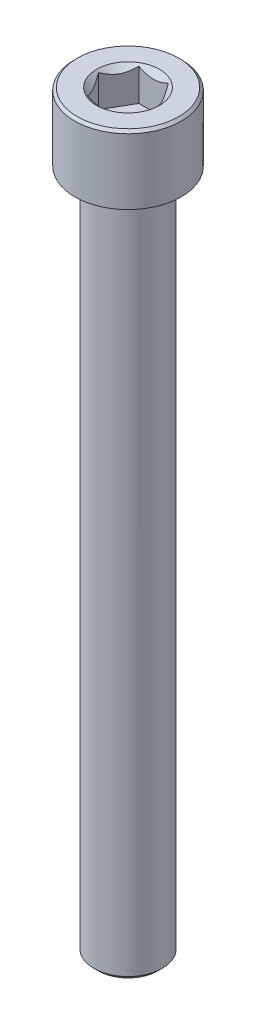
SolidWorks part; units mm, degrees
ref_plane "Płaszczyzna przednia" through (0, 0, 0) normal (0, 0, 1) x (1, 0, 0)
ref_plane "Płaszczyzna górna" through (0, 0, 0) normal (0, 1, 0) x (1, 0, 0)
ref_plane "Płaszczyzna prawa" through (0, 0, 0) normal (1, 0, 0) x (0, 0, -1)
sketch "Szkic1" plane through (0, 0, 0) normal (0, 0, 1) x (1, 0, 0)
  line L0 (0, 0) -> (0, 67.7826) construction
  line L1 (0, 0) -> (-4, 0)
  line L2 (-4, 0) -> (-4, 80)
  line L3 (-4, 80) -> (-6.25, 80)
  line L4 (-6.25, 80) -> (-6.25, 88)
  line L5 (-6.25, 88) -> (0, 88)
  line L6 (0, 88) -> (0, 0)
  dimension "D1" = 12.5
  dimension "D2" = 8
  dimension "D3" = 8
  dimension "D4" = 80
revolve "Obrót1" add sketch "Szkic1" angle 360 about L0
cosmetic thread "Oznaczenie gwintu1" parameters "D2"=6.619
sketch "Szkic2" plane through (0, 88, 0) normal (0, 1, 0) x (1, 0, 0)
  line L0 (0, 0) -> (5.3969, 0) construction
  line L1 (3.4641, 0) -> (1.7321, 3)
  line L2 (1.7321, 3) -> (-1.7321, 3)
  line L3 (-1.7321, 3) -> (-3.4641, 0)
  line L4 (-3.4641, 0) -> (-1.7321, -3)
  line L5 (-1.7321, -3) -> (1.7321, -3)
  line L6 (1.7321, -3) -> (3.4641, 0)
  circle A0 centre (0, 0) radius 3 construction
  dimension "D1" = 6
extrude "Wyciągnięcie1" cut sketch "Szkic2" against normal blind 4
chamfer "Sfazowanie1" distance 0.3 angle 45 1 edges at (0, 88, -6.25)
sketch "Szkic3" plane through (0, 88, 0) normal (0, 1, 0) x (1, 0, 0)
  circle A0 centre (0, 0) radius 3.6817
extrude "Wytnij-wyciągnięcie1" cut sketch "Szkic3" against normal blind 2 draft 45
chamfer "Sfazowanie2" distance 0.5 angle 45 1 edges at (0, 0, -4)
